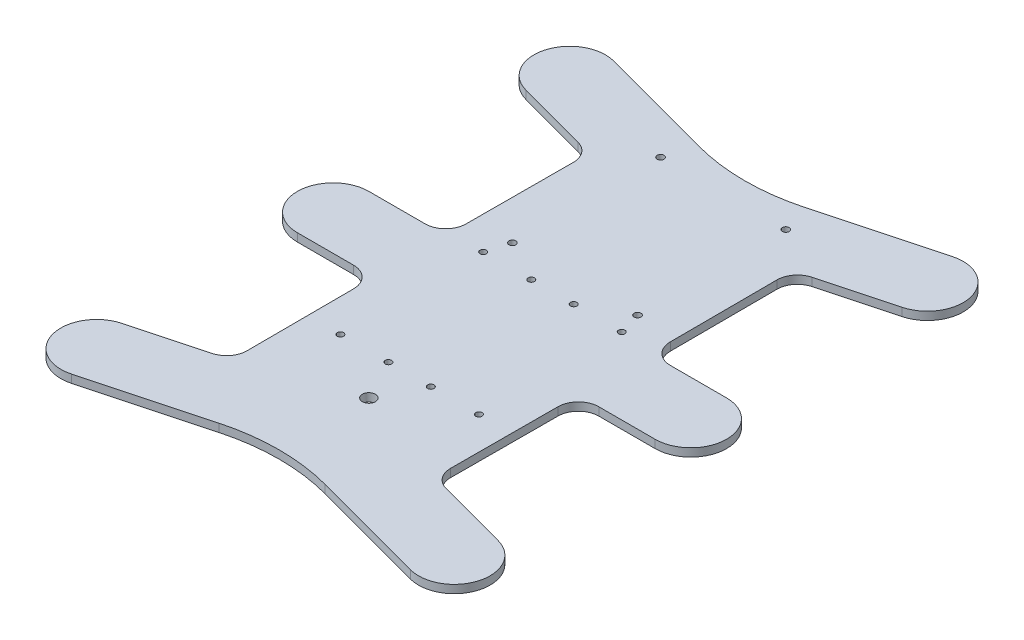
SolidWorks part; units mm, degrees
ref_plane "Front Plane" through (0, 0, 0) normal (0, 0, 1) x (1, 0, 0)
ref_plane "Top Plane" through (0, 0, 0) normal (0, 1, 0) x (1, 0, 0)
ref_plane "Right Plane" through (0, 0, 0) normal (1, 0, 0) x (0, 0, -1)
sketch "Sketch1" plane through (0, 0, 0) normal (0, 1, 0) x (1, 0, 0)
  line L0 (0, 32.1883) -> (0, -21.4181) construction
  line L1 (0, 0) -> (27.1703, 0) construction
  line L2 (-70, 14) -> (-40, 14)
  line L3 (-40, 14) -> (-39.8161, 70)
  line L4 (-39.8161, 70) -> (-73.6235, 79.0587)
  line L5 (-66.3765, 106.1046) -> (0, 88.3191)
  line L10 (-66.3765, 106.1046) -> (-73.6235, 79.0587) construction
  line L12 (-70, 14) -> (-70, -14) construction
  line L14 (-66.3765, -106.1046) -> (0, -88.3191)
  line L15 (-39.8161, -70) -> (-73.6235, -79.0587)
  line L16 (-40, -14) -> (-39.8161, -70)
  line L17 (-70, -14) -> (-40, -14)
  line L18 (66.3765, -106.1046) -> (0, -88.3191)
  line L19 (66.3765, 106.1046) -> (0, 88.3191)
  line L20 (70, 14) -> (70, -14) construction
  line L21 (66.3765, 106.1046) -> (73.6235, 79.0587) construction
  line L22 (70, -14) -> (40, -14)
  line L23 (40, -14) -> (39.8161, -70)
  line L24 (39.8161, -70) -> (73.6235, -79.0587)
  line L25 (39.8161, 70) -> (73.6235, 79.0587)
  line L26 (40, 14) -> (39.8161, 70)
  line L27 (70, 14) -> (40, 14)
  arc A0 (-70, 14) -> (-70, -14) centre (-70, 0) ccw
  arc A1 (-66.3765, 106.1046) -> (-73.6235, 79.0587) centre (-70, 92.5816) ccw
  arc A11 (-66.3765, -106.1046) -> (-73.6235, -79.0587) centre (-70, -92.5816) cw
  arc A18 (66.3765, -106.1046) -> (73.6235, -79.0587) centre (70, -92.5816) ccw
  arc A22 (66.3765, 106.1046) -> (73.6235, 79.0587) centre (70, 92.5816) cw
  arc A23 (70, 14) -> (70, -14) centre (70, 0) cw
  point P118 (-83.523, 96.2051)
  dimension "D2" = 14
  dimension "D3" = 70
  dimension "D1" = 75
  dimension "D5" = 30
  dimension "D6" = 35
  dimension "D7" = 56
extrude "Boss-Extrude1" add sketch "Sketch1" along normal blind 3.175
fillet "Fillet1" radius 80 2 edges at (0, 1.5875, -88.3191) (0, 1.5875, 88.3191)
fillet "Fillet2" radius 8 8 edges at (39.8161, 1.5875, 70) (40, 1.5875, 14) (40, 1.5875, -14) (39.8161, 1.5875, -70) (-39.8161, 1.5875, -70) (-40, 1.5875, -14) (-40, 1.5875, 14) (-39.8161, 1.5875, 70)
sketch "Sketch2" plane through (0, 3.175, 0) normal (0, 1, 0) x (1, 0, 0)
  circle A0 centre (-24.5, 24.6411) radius 1.35 construction
  circle A1 centre (24.5, 24.6411) radius 1.35 construction
  circle A2 centre (24.5, 82.6411) radius 1.35 construction
  circle A3 centre (-24.5, 82.6411) radius 1.35 construction
  circle A4 centre (-24.5, 24.6411) radius 1.35
  circle A5 centre (24.5, 24.6411) radius 1.35
  circle A6 centre (24.5, 82.6411) radius 1.35
  circle A7 centre (-24.5, 82.6411) radius 1.35
extrude "Cut-Extrude1" cut sketch "Sketch2" against normal through all
sketch "Sketch3" plane through (0, 3.175, 0) normal (0, 1, 0) x (1, 0, 0)
  circle A0 centre (-8.3, -40.0589) radius 1.25 construction
  circle A1 centre (-27.1, -40.0589) radius 1.25 construction
  circle A2 centre (-27.1, 15.8411) radius 1.25 construction
  circle A3 centre (-8.3, 15.8411) radius 1.25 construction
  circle A4 centre (8.3, 15.8411) radius 1.25 construction
  circle A5 centre (27.1, 15.8411) radius 1.25 construction
  circle A6 centre (8.3, -40.0589) radius 1.25 construction
  circle A7 centre (27.1, -40.0589) radius 1.25 construction
  circle A8 centre (-8.3, -40.0589) radius 1.25
  circle A9 centre (-27.1, -40.0589) radius 1.25
  circle A10 centre (-27.1, 15.8411) radius 1.25
  circle A11 centre (-8.3, 15.8411) radius 1.25
  circle A12 centre (8.3, 15.8411) radius 1.25
  circle A13 centre (27.1, 15.8411) radius 1.25
  circle A14 centre (8.3, -40.0589) radius 1.25
  circle A15 centre (27.1, -40.0589) radius 1.25
extrude "Cut-Extrude2" cut sketch "Sketch3" against normal through all
sketch "Sketch5" plane through (0, 3.175, 0) normal (0, 1, 0) x (1, 0, 0)
  line L0 (-39.862, -56.0189) -> (39.862, -56.0189) construction
  line L1 (-39.9738, -21.9737) -> (-39.8363, -63.8405) construction
  line L2 (39.8363, -63.8405) -> (39.9738, -21.9737) construction
  line L3 (-27.1, -43.3589) -> (-8.3, -43.3589) construction
  circle A0 centre (0, -56.0189) radius 2.55
  point P6 (0, -56.0189)
  dimension "D2" = 5.1
  dimension "D1" = 12.66
extrude "Cut-Extrude3" cut sketch "Sketch5" against normal through all
